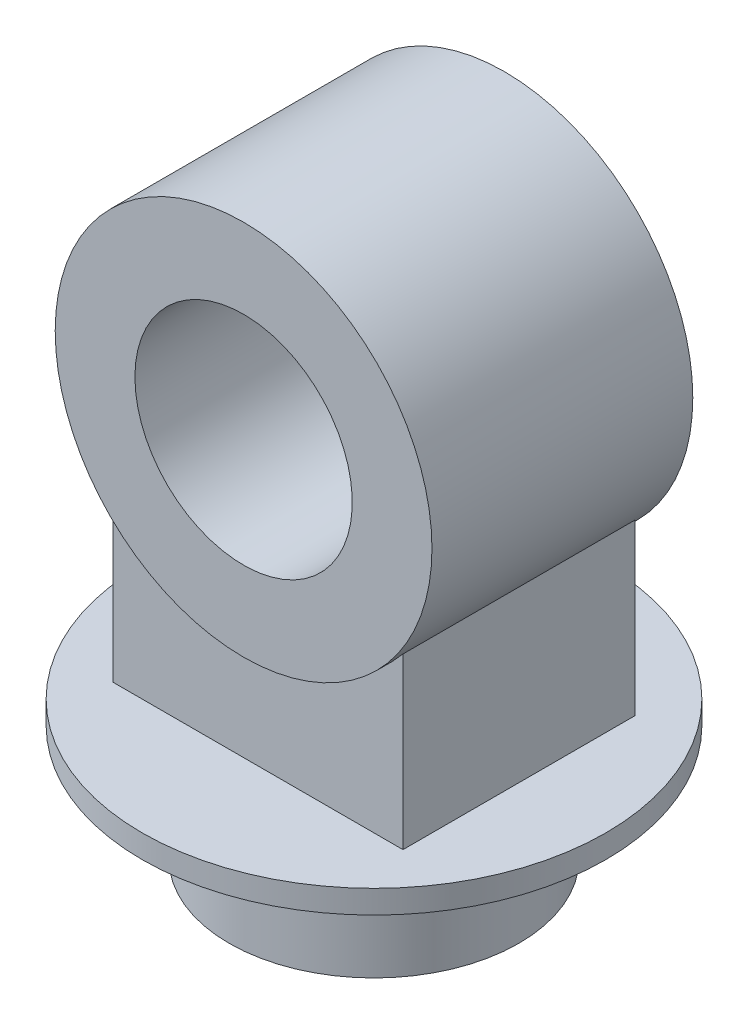
SolidWorks part; units mm, degrees
material "1023 Carbon Steel Sheet (SS)"
ref_plane "Front Plane" through (0, 0, 0) normal (0, 0, 1) x (1, 0, 0)
ref_plane "Top Plane" through (0, 0, 0) normal (0, 1, 0) x (1, 0, 0)
ref_plane "Right Plane" through (0, 0, 0) normal (1, 0, 0) x (0, 0, -1)
sketch "Sketch1" plane through (0, 0, 0) normal (0, 1, 0) x (1, 0, 0)
  circle A0 centre (0, 0) radius 100
extrude "Boss-Extrude1" add sketch "Sketch1" along normal blind 80
sketch "Sketch2" plane through (0, 80, 0) normal (0, 1, 0) x (1, 0, 0)
  circle A0 centre (0, 0) radius 160
extrude "Boss-Extrude2" add sketch "Sketch2" along normal blind 16
sketch "Sketch3" plane through (0, 0, 0) normal (0, 0, 1) x (1, 0, 0)
  line L0 (160, 96) -> (-160, 96) construction
  circle A0 centre (0, 296) radius 75
  circle A1 centre (0, 296) radius 130
  dimension "D1" = 150
  dimension "D2" = 260
  dimension "D3" = 200
extrude "Boss-Extrude3" add sketch "Sketch3" along normal mid plane 180 separate body
sketch "Sketch6" plane through (0, 96, 0) normal (0, 1, 0) x (1, 0, 0)
  line L1 (-100, 80) -> (100, 80)
  line L2 (-100, 80) -> (-100, -80)
  line L3 (-100, -80) -> (100, -80)
  line L4 (100, 80) -> (100, -80)
  line L5 (-100, 80) -> (100, -80) construction
  line L6 (-100, -80) -> (100, 80) construction
  point P0 (0, 0)
  dimension "D1" = 160
  dimension "D2" = 200
extrude "Boss-Extrude4" add sketch "Sketch6" along normal up to next
